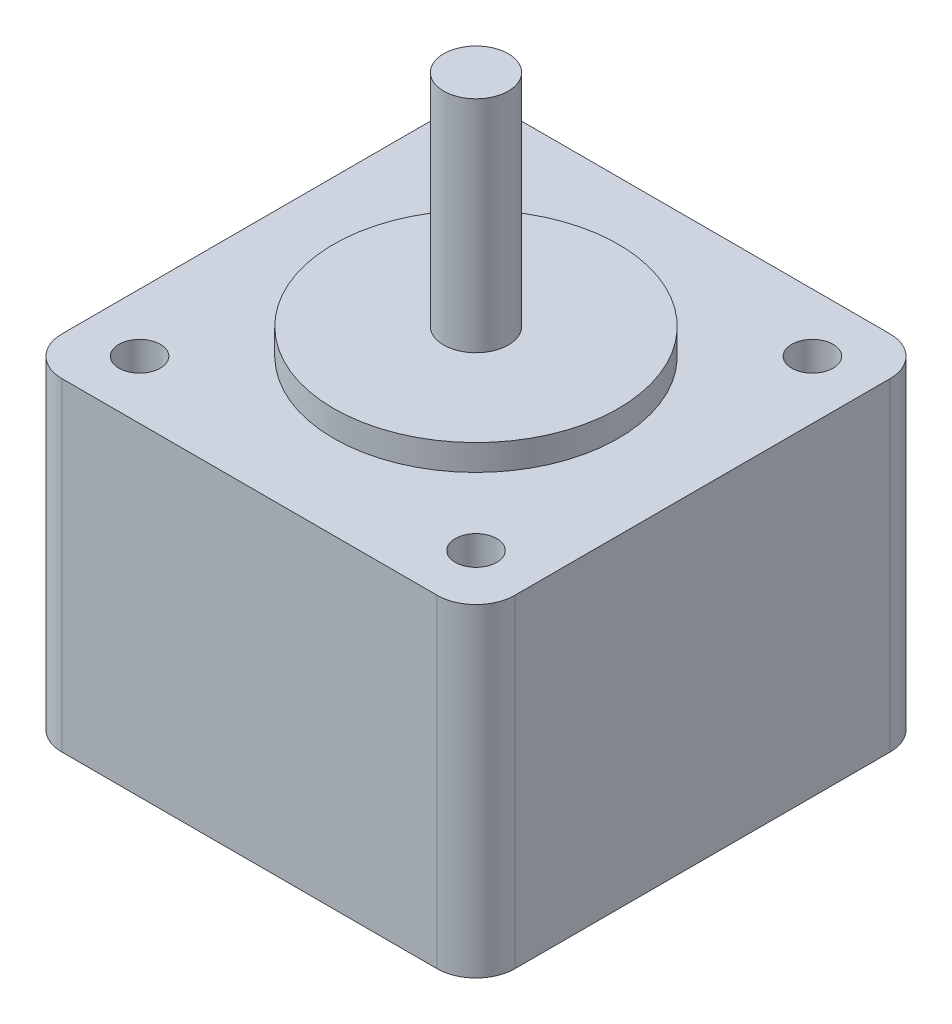
SolidWorks part; units mm, degrees
material "延性铁"
ref_plane "前视基准面" through (0, 0, 0) normal (0, 0, 1) x (1, 0, 0)
ref_plane "上视基准面" through (0, 0, 0) normal (0, 1, 0) x (1, 0, 0)
ref_plane "右视基准面" through (0, 0, 0) normal (1, 0, 0) x (0, 0, -1)
sketch "草图1" plane through (0, 0, 0) normal (0, 1, 0) x (1, 0, 0)
  line L1 (-14.5, 17.5) -> (14.5, 17.5)
  line L2 (-17.5, 14.5) -> (-17.5, -14.5)
  line L3 (-14.5, -17.5) -> (14.5, -17.5)
  line L4 (17.5, 14.5) -> (17.5, -14.5)
  line L5 (-17.5, 17.5) -> (17.5, -17.5) construction
  line L6 (-17.5, -17.5) -> (17.5, 17.5) construction
  arc A0 (-17.5, -14.5) -> (-14.5, -17.5) centre (-14.5, -14.5) ccw
  arc A1 (14.5, -17.5) -> (17.5, -14.5) centre (14.5, -14.5) ccw
  arc A2 (17.5, 14.5) -> (14.5, 17.5) centre (14.5, 14.5) ccw
  arc A3 (-17.5, 14.5) -> (-14.5, 17.5) centre (-14.5, 14.5) cw
  point P0 (0, 0)
  dimension "D3" = 3
  dimension "D1" = 35
  dimension "D2" = 35
extrude "凸台-拉伸1" add sketch "草图1" along normal blind 25
ref_plane "基准面1" through (0, 25, 0) normal (0, 1, 0) x (1, 0, 0)
sketch "草图2" plane through (0, 25, 0) normal (0, 1, 0) x (1, 0, 0)
  circle A0 centre (0, 0) radius 11
  dimension "D1" = 22
extrude "凸台-拉伸2" add sketch "草图2" along normal blind 2
ref_plane "基准面2" through (0, 27, 0) normal (0, 1, 0) x (1, 0, 0)
sketch "草图3" plane through (0, 27, 0) normal (0, 1, 0) x (1, 0, 0)
  circle A0 centre (0, 0) radius 2.5
  dimension "D1" = 5
extrude "凸台-拉伸3" add sketch "草图3" along normal blind 17
ref_plane "基准面3" through (0, 0, 0) normal (0, -1, 0) x (-1, 0, 0)
sketch "草图4" plane through (0, 25, 0) normal (0, 1, 0) x (1, 0, 0)
  line L1 (-13, 13) -> (13, 13) construction
  line L2 (-13, 13) -> (-13, -13) construction
  line L3 (-13, -13) -> (13, -13) construction
  line L4 (13, 13) -> (13, -13) construction
  line L5 (-13, 13) -> (13, -13) construction
  line L6 (-13, -13) -> (13, 13) construction
  circle A0 centre (-13, 13) radius 1.6
  circle A1 centre (13, 13) radius 1.6
  circle A2 centre (13, -13) radius 1.6
  circle A3 centre (-13, -13) radius 1.6
  point P0 (0, 0)
  dimension "D3" = 3.2
  dimension "D4" = 3.2
  dimension "D5" = 3.2
  dimension "D6" = 3.2
  dimension "D1" = 26
  dimension "D2" = 26
extrude "切除-拉伸1" cut sketch "草图4" against normal blind 5
